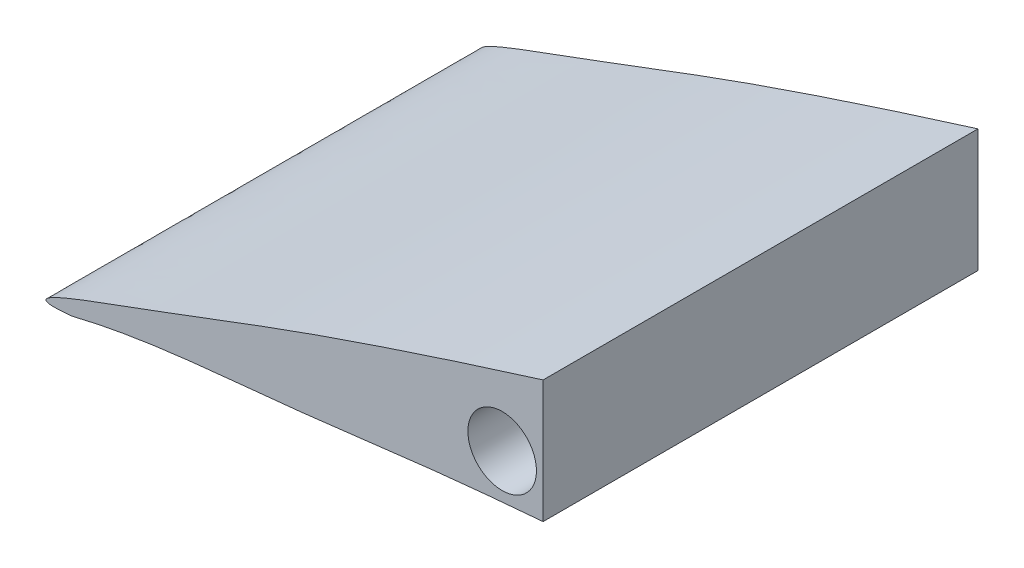
SolidWorks part; units mm, degrees
ref_plane "Front Plane" through (0, 0, 0) normal (0, 0, 1) x (1, 0, 0)
ref_plane "Top Plane" through (0, 0, 0) normal (0, 1, 0) x (1, 0, 0)
ref_plane "Right Plane" through (0, 0, 0) normal (1, 0, 0) x (0, 0, -1)
sketch "Sketch1" plane through (0, 0, 0) normal (0, 0, 1) x (1, 0, 0)
  line L0 (42.9183, -0.4477) -> (42.9183, 8.2631)
  circle A0 centre (-19.1025, -6.0109) radius 2.127
  circle A1 centre (12.6475, 4.4031) radius 2.127
  arc A2 (37.8951, -5.5274) -> (42.9183, -0.4477) centre (37.8383, -0.4477) ccw
  arc A3 (42.9183, 8.2631) -> (36.6811, 13.2095) centre (37.8383, 8.2631) ccw
  circle A4 centre (33.8935, 3.4217) radius 2.032
  spline S0 degree 3 poles (36.6811, 13.2095) (19.8298, 9.2672) (-2.0736, 3.8441) (-31.0965, -5.5459) (-39.3168, -8.8066) (-49.5156, -12.4957) (-45.7725, -12.1069) knots 0.118069 0.118069 0.118069 0.118069 0.630725 0.824214 0.940085 1 1 1 1
  spline S1 degree 3 poles (-45.7725, -12.1069) (-41.3374, -10.9993) (-33.8316, -10.53) (-20.4835, -8.7075) (-8.8734, -8.0192) (11.5246, -6.0282) (26.0673, -5.6598) (37.8951, -5.5274) knots 0 0 0 0 0.144322 0.237948 0.427123 0.512832 0.887818 0.887818 0.887818 0.887818
extrude "Boss-Extrude1" add sketch "Sketch1" along normal blind 26.9875
sketch "Sketch2" plane through (0, 0, 26.9875) normal (0, 0, 1) x (1, 0, 0)
  line L1 (-16.5625, 14.1188) -> (88.17, 14.1188)
  line L2 (-16.5625, 14.1188) -> (-16.5625, -18.8296)
  line L3 (-16.5625, -18.8296) -> (88.17, -18.8296)
  line L4 (88.17, 14.1188) -> (88.17, -18.8296)
  dimension "D1" = 29.21
extrude "Cut-Extrude1" cut sketch "Sketch2" against normal blind 27.0764
